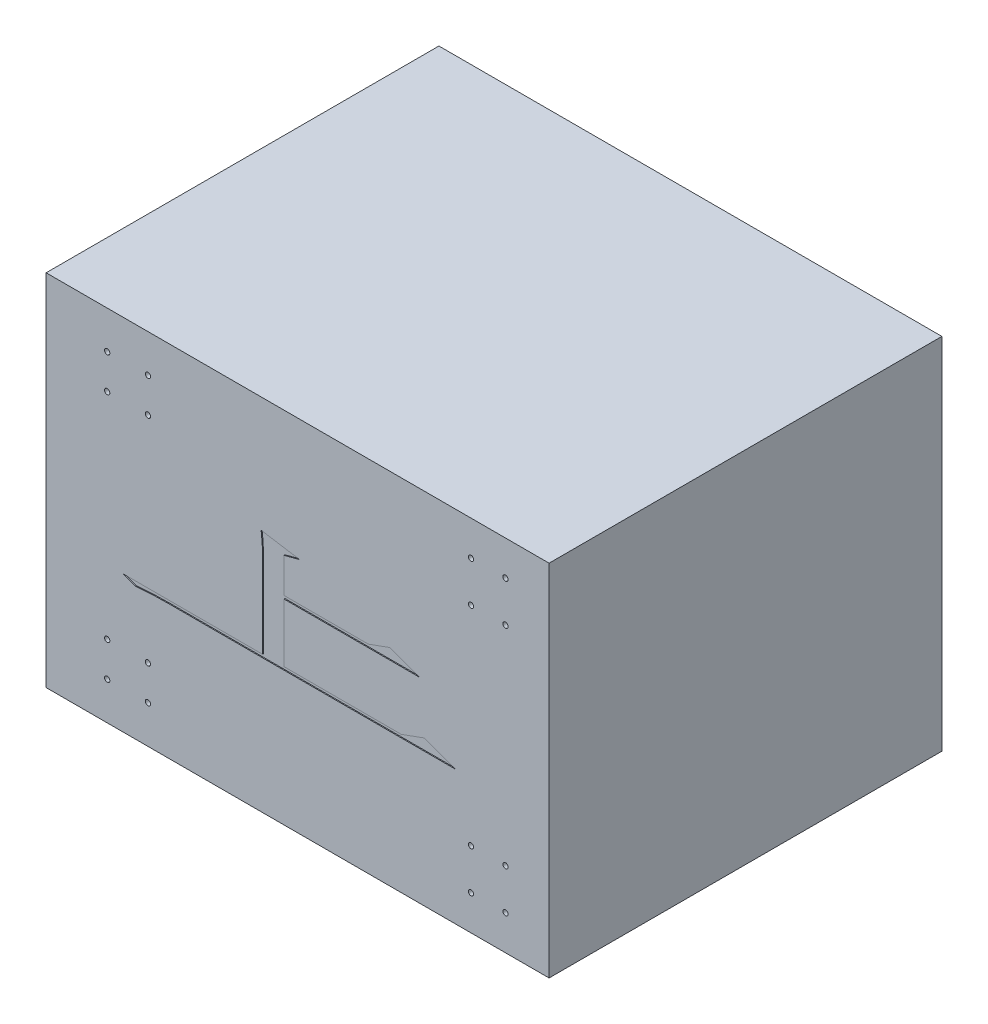
SolidWorks part; units mm, degrees
ref_plane "前视基准面" through (0, 0, 0) normal (0, 0, 1) x (1, 0, 0)
ref_plane "上视基准面" through (0, 0, 0) normal (0, 1, 0) x (1, 0, 0)
ref_plane "右视基准面" through (0, 0, 0) normal (1, 0, 0) x (0, 0, -1)
sketch "草图1" plane through (0, 0, 0) normal (0, 0, 1) x (1, 0, 0)
  line L1 (525, 375) -> (-525, 375)
  line L2 (525, 375) -> (525, -375)
  line L3 (525, -375) -> (-525, -375)
  line L4 (-525, 375) -> (-525, -375)
  line L5 (525, 375) -> (-525, -375) construction
  line L6 (525, -375) -> (-525, 375) construction
  point P0 (0, 0)
  dimension "D1" = 1050
  dimension "D2" = 750
extrude "凸台-拉伸1" add sketch "草图1" along normal mid plane 820
sketch "草图2" plane through (0, 0, 410) normal (0, 0, 1) x (1, 0, 0)
  text T0 "上" font "Century Gothic" height 200
extrude "切除-拉伸1" cut sketch "草图2" against normal blind 2
sketch "草图3" plane through (0, -375, 0) normal (0, -1, 0) x (1, 0, 0)
  line L0 (-525, -200) -> (525, -200) construction
  line L1 (-525, 410) -> (-525, -410) construction
  line L2 (525, 410) -> (525, -410) construction
  text T0 " 柴油机" font "Century Gothic" height 200
  dimension "D1" = 200
extrude "切除-拉伸2" cut sketch "草图3" against normal blind 2
sketch "草图4" plane through (0, 0, -410) normal (0, 0, -1) x (-1, 0, 0)
  line L0 (-525, -375) -> (-525, 375) construction
  line L1 (-525, 375) -> (525, 375) construction
  line L2 (525, 375) -> (525, -375) construction
  circle A0 centre (-434, 302.5) radius 5.5
  circle A1 centre (-362, 302.5) radius 5.5
  circle A2 centre (-434, 217.5) radius 5.5
  circle A3 centre (-362, 217.5) radius 5.5
  circle A4 centre (312.5, 296) radius 5.5
  circle A5 centre (397.5, 296) radius 5.5
  circle A6 centre (312.5, 224) radius 5.5
  circle A7 centre (397.5, 224) radius 5.5
  circle A8 centre (-434, -217.5) radius 5.5
  circle A9 centre (-362, -217.5) radius 5.5
  circle A10 centre (-434, -302.5) radius 5.5
  circle A11 centre (-362, -302.5) radius 5.5
  circle A12 centre (312.5, -224) radius 5.5
  circle A13 centre (397.5, -224) radius 5.5
  circle A14 centre (312.5, -296) radius 5.5
  circle A15 centre (397.5, -296) radius 5.5
  point P38 (0, 0)
  dimension "D1" = 11
  dimension "D2" = 72
  dimension "D7" = 435
  dimension "D11" = 72
  dimension "D12" = 448
  dimension "D13" = 79
  dimension "D3" = 91
  dimension "D4" = 85
  dimension "D5" = 85
  dimension "D6" = 72.5
  dimension "D8" = 85
  dimension "D9" = 127.5
  dimension "D10" = 72
extrude "切除-拉伸3" cut sketch "草图4" against normal through all
